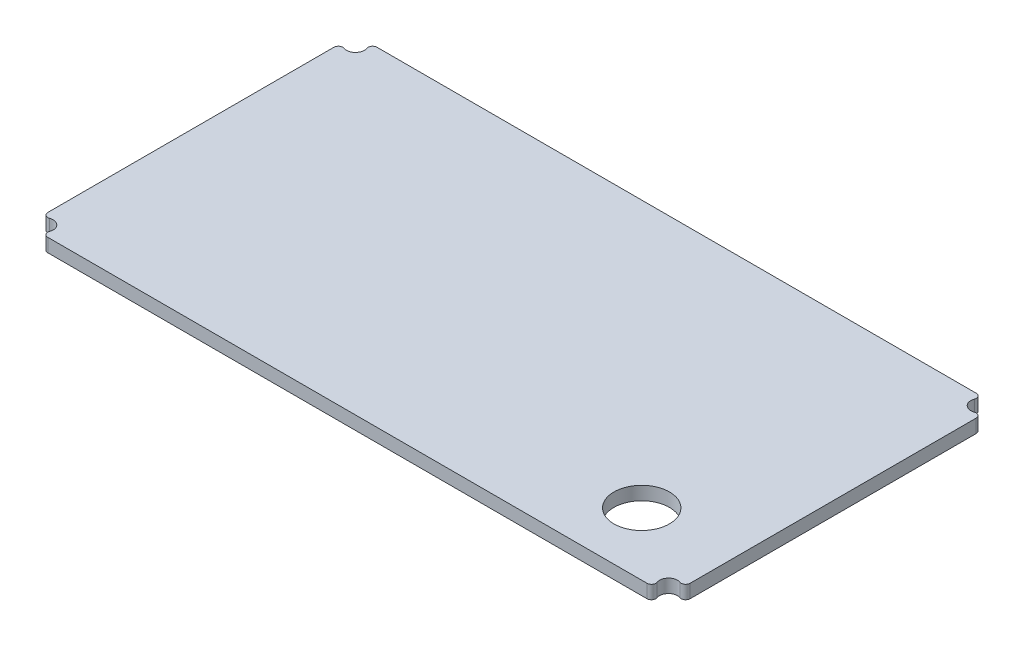
SolidWorks part; units mm, degrees
ref_plane "Front Plane" through (0, 0, 0) normal (0, 0, 1) x (1, 0, 0)
ref_plane "Top Plane" through (0, 0, 0) normal (0, 1, 0) x (1, 0, 0)
ref_plane "Right Plane" through (0, 0, 0) normal (1, 0, 0) x (0, 0, -1)
sketch "Sketch1" plane through (0, 0, 0) normal (0, 1, 0) x (1, 0, 0)
  line L1 (2.4142, 0) -> (69.3858, 0)
  line L2 (0, 2.4142) -> (0, 34.3858)
  line L3 (2.4142, 36.8) -> (69.3858, 36.8)
  line L4 (71.8, 2.4142) -> (71.8, 34.3858)
  arc A0 (0.6667, 34.8572) -> (1.9428, 36.1333) centre (1, 35.8) ccw
  arc A1 (1.9428, 0.6667) -> (0.6667, 1.9428) centre (1, 1) ccw
  arc A2 (71.1333, 1.9428) -> (69.8572, 0.6667) centre (70.8, 1) ccw
  arc A3 (69.8572, 36.1333) -> (71.1333, 34.8572) centre (70.8, 35.8) ccw
  arc A4 (69.8572, 36.1333) -> (69.3858, 36.8) centre (69.3858, 36.3) ccw
  arc A5 (71.8, 34.3858) -> (71.1333, 34.8572) centre (71.3, 34.3858) ccw
  arc A6 (71.1333, 1.9428) -> (71.8, 2.4142) centre (71.3, 2.4142) ccw
  arc A7 (69.8572, 0.6667) -> (69.3858, 0) centre (69.3858, 0.5) cw
  arc A8 (2.4142, 0) -> (1.9428, 0.6667) centre (2.4142, 0.5) cw
  arc A9 (0, 2.4142) -> (0.6667, 1.9428) centre (0.5, 2.4142) ccw
  arc A10 (2.4142, 36.8) -> (1.9428, 36.1333) centre (2.4142, 36.3) ccw
  arc A11 (0, 34.3858) -> (0.6667, 34.8572) centre (0.5, 34.3858) cw
  dimension "D3" = 1
  dimension "D7" = 1
  dimension "D2" = 0.5
  dimension "D4" = 1
  dimension "D5" = 1
  dimension "D6" = 1
  dimension "D8" = 1
  dimension "D9" = 1
  dimension "D10" = 1
extrude "Boss-Extrude1" add sketch "Sketch1" along normal blind 1.5
sketch "Sketch2" plane through (0, 1.5, 0) normal (0, 1, 0) x (1, 0, 0)
  line L0 (2.4142, 0) -> (69.3858, 0) construction
  line L1 (71.8, 2.4142) -> (71.8, 34.3858) construction
  circle A0 centre (61.8, 7) radius 3.1
  dimension "D1" = 7
  dimension "D2" = 10
extrude "Cut-Extrude1" cut sketch "Sketch2" against normal blind 1.5
